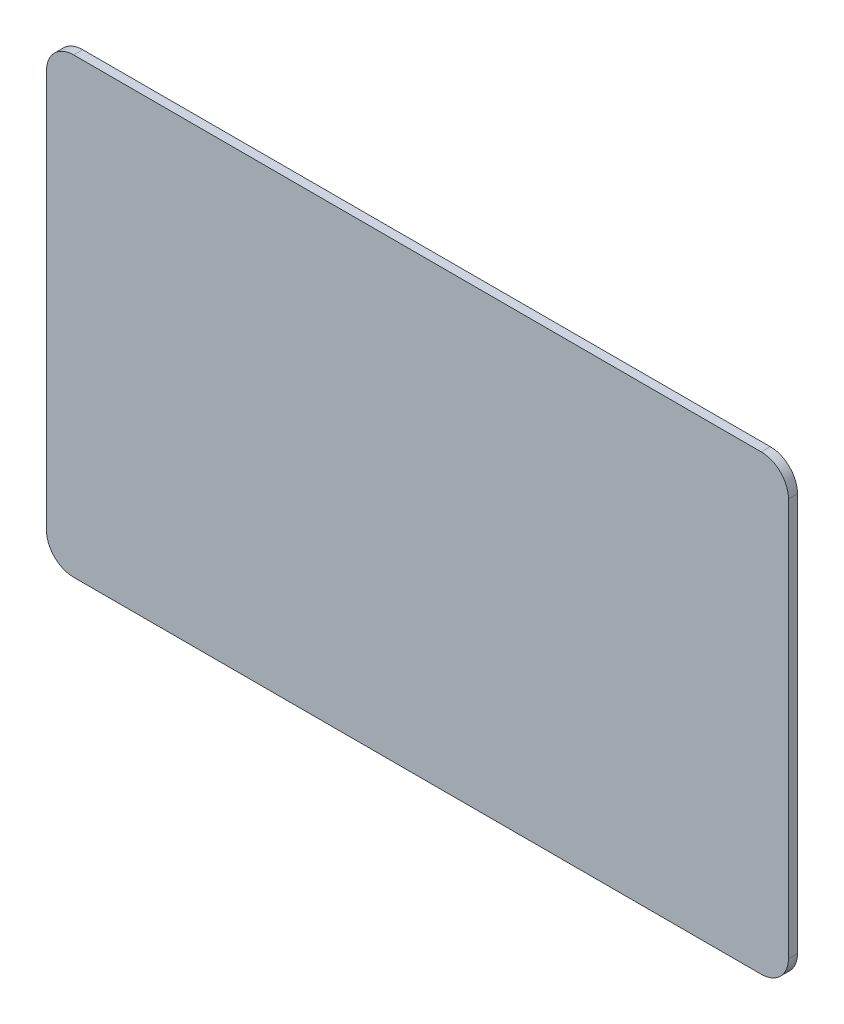
SolidWorks part; units mm, degrees
material "Thornel Mat VMA"
ref_plane "前视基准面" through (0, 0, 0) normal (0, 0, 1) x (1, 0, 0)
ref_plane "上视基准面" through (0, 0, 0) normal (0, 1, 0) x (1, 0, 0)
ref_plane "右视基准面" through (0, 0, 0) normal (1, 0, 0) x (0, 0, -1)
other "Configuration Table"
sketch "草图1" plane through (0, 0, 0) normal (0, 0, 1) x (1, 0, 0)
  line L1 (-41, 25) -> (41, 25)
  line L2 (-41, 25) -> (-41, -25)
  line L3 (-41, -25) -> (41, -25)
  line L4 (41, 25) -> (41, -25)
  line L5 (-41, 25) -> (41, -25) construction
  line L6 (-41, -25) -> (41, 25) construction
  point P0 (0, 0)
  dimension "D1" = 82
  dimension "D2" = 50
extrude "凸台-拉伸1" add sketch "草图1" along normal blind 1
fillet "圆角1" radius 3 4 edges at (41, -25, 0.5) (41, 25, 0.5) (-41, -25, 0.5) (-41, 25, 0.5)
